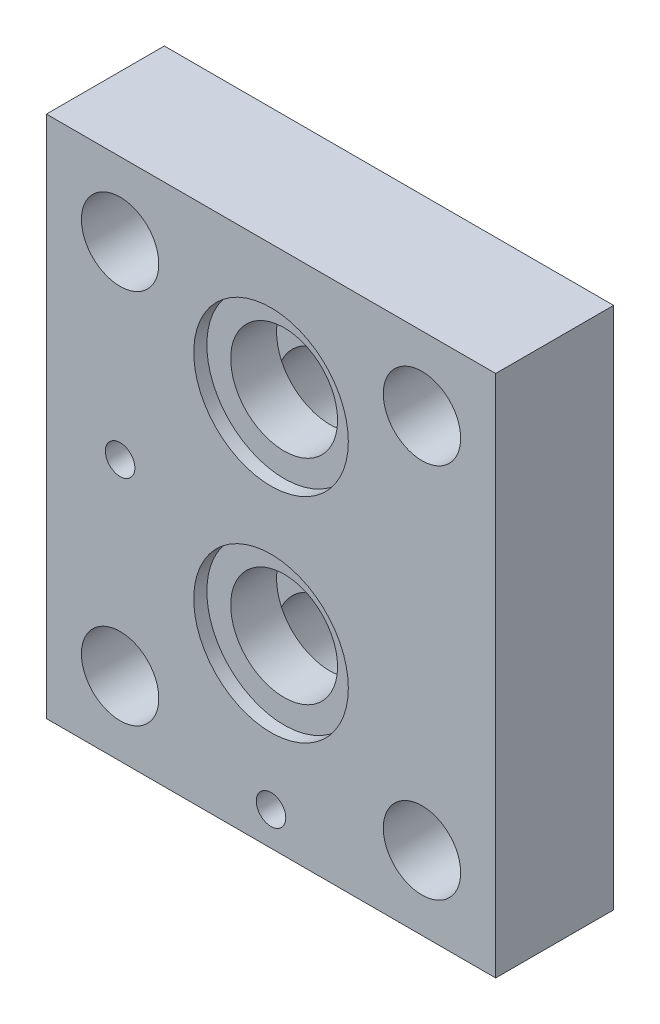
SolidWorks part; units mm, degrees
ref_plane "Front Plane" through (0, 0, 0) normal (1, 0, 0) x (0, 1, 0)
ref_plane "Top Plane" through (0, 0, 0) normal (0, 0, 1) x (0, 1, 0)
ref_plane "Right Plane" through (0, 0, 0) normal (0, 1, 0) x (-1, 0, 0)
sketch "Sketch1" plane through (0, 0, 0) normal (0, 0, 1) x (0, 1, 0)
  line L1 (-56.388, -48.387) -> (56.388, -48.387)
  line L2 (-56.388, -48.387) -> (-56.388, 48.387)
  line L3 (-56.388, 48.387) -> (56.388, 48.387)
  line L4 (56.388, -48.387) -> (56.388, 48.387)
  line L5 (-56.388, -48.387) -> (56.388, 48.387) construction
  line L6 (-56.388, 48.387) -> (56.388, -48.387) construction
  point P0 (0, 0)
extrude "Boss-Extrude1" add sketch "Sketch1" along normal mid plane 25.4
sketch "Sketch2" plane through (0, 0, 0) normal (0, 0, 1) x (0, 1, 0)
  circle A0 centre (-40.513, -32.512) radius 8.3344
extrude "Cut-Extrude2" cut sketch "Sketch2" along normal up to next from offset 12.7
sketch "Sketch3" plane through (0, 0, 0) normal (0, 0, 1) x (0, 1, 0)
  circle A0 centre (40.513, -32.512) radius 8.3344
  circle A1 centre (-40.513, 32.512) radius 8.3344
  circle A2 centre (40.513, 32.512) radius 8.3344
extrude "Cut-Extrude4" cut sketch "Sketch3" along normal up to next from offset 12.7
sketch "Sketch4" plane through (0, 0, 0) normal (0, 0, 1) x (0, 1, 0)
  circle A0 centre (-27.813, 0) radius 11.5094
extrude "Cut-Extrude6" cut sketch "Sketch4" along normal blind 12.7 from offset 12.7
sketch "Sketch5" plane through (0, 0, 0) normal (0, 0, 1) x (0, 1, 0)
  circle A0 centre (18.161, 0) radius 11.5094
extrude "Cut-Extrude8" cut sketch "Sketch5" along normal blind 12.7 from offset 12.7
sketch "Sketch6" plane through (0, 0, 0) normal (0, 0, 1) x (0, 1, 0)
  circle A0 centre (-18.161, 0) radius 11.5094
extrude "Cut-Extrude10" cut sketch "Sketch6" against normal blind 12.7 from offset 12.7
sketch "Sketch7" plane through (0, 0, 0) normal (0, 0, 1) x (0, 1, 0)
  circle A0 centre (27.813, 0) radius 11.5094
extrude "Cut-Extrude12" cut sketch "Sketch7" against normal blind 12.7 from offset 12.7
sketch "Sketch8" plane through (0, 0, 0) normal (0, 0, 1) x (0, 1, 0)
  circle A0 centre (-18.161, 0) radius 16.6497
extrude "Cut-Extrude14" cut sketch "Sketch8" against normal blind 2.8194 from offset 12.7
sketch "Sketch9" plane through (0, 0, 0) normal (0, 0, 1) x (0, 1, 0)
  circle A0 centre (27.813, 0) radius 16.6497
extrude "Cut-Extrude16" cut sketch "Sketch9" against normal blind 2.8194 from offset 12.7
sketch "Sketch10" plane through (0, 0, 0) normal (0, 0, 1) x (0, 1, 0)
  circle A0 centre (49.149, 0) radius 3.5719
extrude "Cut-Extrude18" cut sketch "Sketch10" along normal blind 7.874 from offset 12.7
sketch "Sketch11" plane through (0, 0, 0) normal (0, 0, 1) x (0, 1, 0)
  circle A0 centre (0.127, -32.512) radius 3.5719
extrude "Cut-Extrude20" cut sketch "Sketch11" along normal blind 7.874 from offset 12.7
sketch "Sketch12" plane through (0, 0, 0) normal (0, 0, 1) x (0, 1, 0)
  circle A0 centre (-49.149, 0) radius 3.175
extrude "Cut-Extrude22" cut sketch "Sketch12" against normal blind 7.874 from offset 12.7
sketch "Sketch13" plane through (0, 0, 0) normal (0, 0, 1) x (0, 1, 0)
  circle A0 centre (-0.127, 32.512) radius 3.175
extrude "Cut-Extrude24" cut sketch "Sketch13" against normal blind 7.874 from offset 12.7
